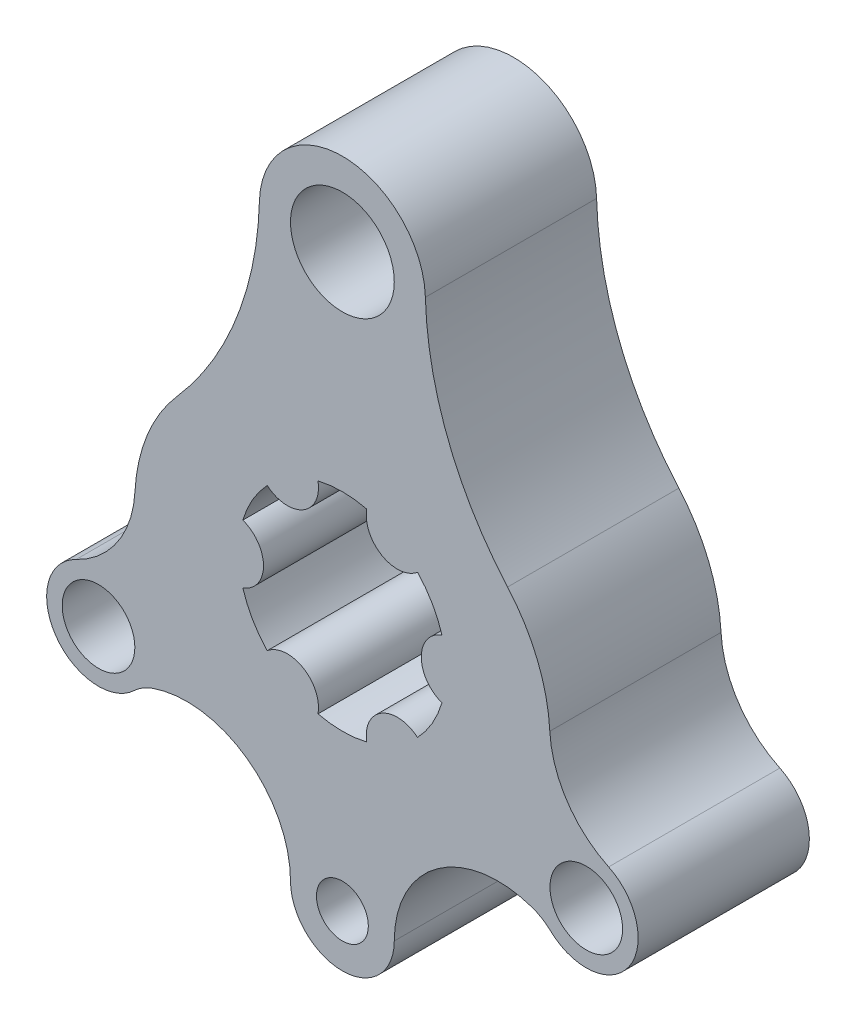
SolidWorks part; units mm, degrees
ref_plane "Front Plane" through (0, 0, 0) normal (0, 0, 1) x (1, 0, 0)
ref_plane "Top Plane" through (0, 0, 0) normal (0, 1, 0) x (1, 0, 0)
ref_plane "Right Plane" through (0, 0, 0) normal (1, 0, 0) x (0, 0, -1)
sketch "Sketch1" plane through (0, 0, 0) normal (0, 0, 1) x (1, 0, 0)
  line L0 (0, -667.1532) -> (0, 32690.5074) construction
  line L1 (-667.1532, 0) -> (32690.5074, 0) construction
  line L2 (37.3228, -36.2669) -> (56.6772, -15.7331) construction
  line L3 (56.6772, -15.7331) -> (37.3228, -36.2669) construction
  line L4 (0, 0) -> (5.2373, 0) construction
  circle A0 centre (0, 60) radius 10
  arc A1 (-16, 60) -> (15.994, 60.4369) centre (0, 60) cw
  arc A2 (31.8405, 20) -> (39.9772, 0) centre (7.0237, -1.7514) cw
  arc A4 (15.994, 60.4369) -> (31.8405, 20) centre (79.9702, 62.1846) ccw
  arc A5 (39.9772, 0) -> (51.3163, -16.9795) centre (59.949, 1.0615) ccw
  arc A6 (51.3163, -16.9795) -> (40.141, -33.277) centre (47, -26) cw
  arc A7 (36.564, -31.1078) -> (40.141, -33.277) centre (33.282, -40.5539) cw
  circle A8 centre (0, -50) radius 5
  circle A9 centre (47, -26) radius 7
  arc A10 (-10, -50) -> (10, -50) centre (0, -50) ccw
  arc A11 (36.564, -31.1078) -> (10, -50) centre (30, -50) ccw
  arc A12 (-36.564, -31.1078) -> (-40.141, -33.277) centre (-33.282, -40.5539) ccw
  arc A13 (-36.564, -31.1078) -> (-10, -50) centre (-30, -50) cw
  circle A14 centre (-47, -26) radius 7
  arc A15 (-51.3163, -16.9795) -> (-40.141, -33.277) centre (-47, -26) ccw
  arc A16 (-39.9772, 0) -> (-51.3163, -16.9795) centre (-59.949, 1.0615) cw
  arc A17 (-31.8405, 20) -> (-39.9772, 0) centre (-7.0237, -1.7514) ccw
  arc A18 (-15.994, 60.4369) -> (-31.8405, 20) centre (-79.9702, 62.1846) cw
  arc A19 (-4.6988, 19.4402) -> (4.6988, 19.4402) centre (0, 0) cw
  arc A21 (14.4863, 13.7894) -> (19.1851, 5.6508) centre (0, 0) cw
  arc A22 (19.1851, -5.6508) -> (14.4863, -13.7894) centre (0, 0) cw
  arc A23 (4.6988, -19.4402) -> (-4.6988, -19.4402) centre (0, 0) cw
  arc A24 (-14.4863, -13.7894) -> (-19.1851, -5.6508) centre (0, 0) cw
  arc A25 (-19.1851, 5.6508) -> (-14.4863, 13.7894) centre (0, 0) cw
  arc A26 (4.6988, 19.4402) -> (14.4863, 13.7894) centre (10.601, 18.3615) ccw
  arc A27 (19.1851, 5.6508) -> (19.1851, -5.6508) centre (21.202, 0) ccw
  arc A28 (14.4863, -13.7894) -> (4.6988, -19.4402) centre (10.601, -18.3615) ccw
  arc A29 (-4.6988, -19.4402) -> (-14.4863, -13.7894) centre (-10.601, -18.3615) ccw
  arc A30 (-19.1851, -5.6508) -> (-19.1851, 5.6508) centre (-21.202, 0) ccw
  arc A31 (-14.4863, 13.7894) -> (-4.6988, 19.4402) centre (-10.601, 18.3615) ccw
  point P13 (0, 20)
  point P29 (47, -26)
  point P45 (0, 0)
  point P47 (-10.2699, 17.2126)
  point P48 (0, 0)
  point P60 (0, 0)
  point P77 (0, 0)
  dimension "D1" = 20
  dimension "D3" = 16
  dimension "D4" = 20
  dimension "D5" = 33
  dimension "D6" = 64
  dimension "D7" = 10
  dimension "D8" = 10
  dimension "D9" = 10
  dimension "D10" = 14
  dimension "D13" = 26
  dimension "D14" = 20
  dimension "D15" = 20
  dimension "D16" = 10
  dimension "D17" = 6
  dimension "D18" = 6
  dimension "D2" = 60
  dimension "D11" = 47
  dimension "D12" = 24
  dimension "D20" = 4.6988
  dimension "D21" = 7.0237
  dimension "D19" = 6
extrude "Boss-Extrude1" add sketch "Sketch1" along normal blind 33
